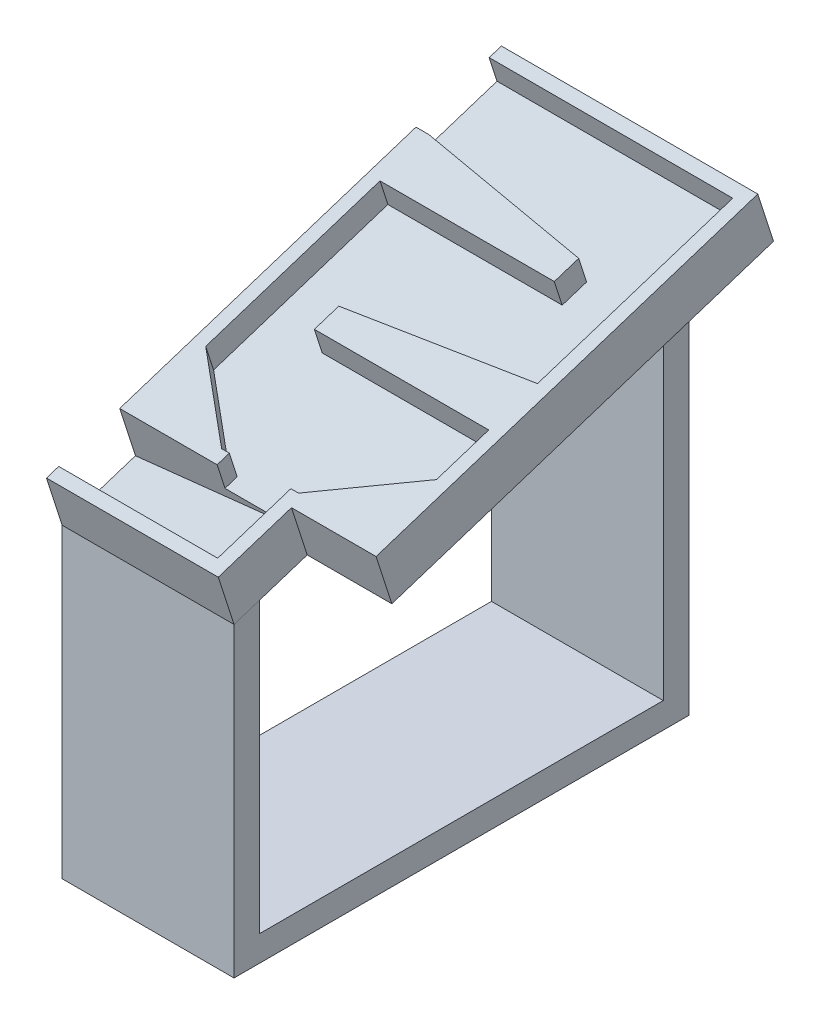
SolidWorks part; units mm, degrees
ref_plane "前基準面" through (0, 0, 0) normal (0, 0, 1) x (1, 0, 0)
ref_plane "上基準面" through (0, 0, 0) normal (0, 1, 0) x (1, 0, 0)
ref_plane "右基準面" through (0, 0, 0) normal (1, 0, 0) x (0, 0, -1)
sketch "草圖1" plane through (0, 0, 0) normal (1, 0, 0) x (0, 0, -1)
  line L0 (0, 0) -> (74.4311, 24)
  line L1 (74.4311, 24) -> (77.5, 14.4825)
  line L2 (77.5, 14.4825) -> (3.0689, -9.5175)
  line L3 (3.0689, -9.5175) -> (0, 0)
  dimension "D1" = 24
  dimension "D2" = 10
  dimension "D3" = 77.5
extrude "填料-伸長1" add sketch "草圖1" along normal blind 50
sketch "草圖2" plane through (0, 0, 0) normal (0, 0.9517, 0.3069) x (1, 0, 0)
  line L0 (0, 78.2048) -> (0, 0) construction
  line L1 (2.5, 75.7048) -> (47.5, 75.7048)
  line L2 (2.5, 75.7048) -> (2.5, 2.5)
  line L3 (2.5, 2.5) -> (47.5, 2.5)
  line L4 (47.5, 75.7048) -> (47.5, 2.5)
  line L5 (50, 78.2048) -> (50, 0) construction
  line L6 (50, 78.2048) -> (0, 78.2048) construction
  line L7 (50, 0) -> (0, 0) construction
  dimension "D1" = 2.5
  dimension "D2" = 2.5
  dimension "D3" = 2.5
  dimension "D4" = 2.5
extrude "除料-伸長1" cut sketch "草圖2" against normal blind 5
sketch "草圖3" plane through (0, -4.7587, -1.5344) normal (0, 0.9517, 0.3069) x (1, 0, 0)
  line L0 (2.5, 75.7048) -> (2.5, 2.5) construction
  line L1 (47.5, 75.7048) -> (2.5, 75.7048) construction
  line L2 (47.5, 2.5) -> (47.5, 75.7048) construction
  line L5 (50, 0) -> (0, 0) construction
  line L6 (0, 78.2048) -> (0, 0) construction
  circle A0 centre (18.5, 59.7048) radius 2.5
  circle A1 centre (21.75, 59.7048) radius 2.5
  circle A2 centre (25, 59.7048) radius 2.5
  circle A3 centre (28.25, 59.7048) radius 2.5
  circle A4 centre (31.5, 59.7048) radius 2.5
  circle A5 centre (19, 55.7229) radius 2.5
  circle A6 centre (22.25, 55.7229) radius 2.5
  circle A7 centre (25.5, 55.7229) radius 2.5
  circle A8 centre (28.75, 55.7229) radius 2.5
  circle A9 centre (32, 55.7229) radius 2.5
  circle A10 centre (19.5, 51.741) radius 2.5
  circle A11 centre (22.75, 51.741) radius 2.5
  circle A12 centre (26, 51.741) radius 2.5
  circle A13 centre (29.25, 51.741) radius 2.5
  circle A14 centre (32.5, 51.741) radius 2.5
  circle A15 centre (20, 47.7591) radius 2.5
  circle A16 centre (23.25, 47.7591) radius 2.5
  circle A17 centre (26.5, 47.7591) radius 2.5
  circle A18 centre (29.75, 47.7591) radius 2.5
  circle A19 centre (33, 47.7591) radius 2.5
  circle A20 centre (20.5, 43.7772) radius 2.5
  circle A21 centre (23.75, 43.7772) radius 2.5
  circle A22 centre (27, 43.7772) radius 2.5
  circle A23 centre (30.25, 43.7772) radius 2.5
  circle A24 centre (33.5, 43.7772) radius 2.5
  circle A25 centre (21, 39.7953) radius 2.5
  circle A26 centre (24.25, 39.7953) radius 2.5
  circle A27 centre (27.5, 39.7953) radius 2.5
  circle A28 centre (30.75, 39.7953) radius 2.5
  circle A29 centre (34, 39.7953) radius 2.5
  circle A35 centre (24.75, 35.8134) radius 2.5 [skipped]
  circle A36 centre (28, 35.8134) radius 2.5 [skipped]
  circle A37 centre (31.25, 35.8134) radius 2.5 [skipped]
  circle A38 centre (34.5, 35.8134) radius 2.5 [skipped]
  circle A39 centre (21.5, 35.8134) radius 2.5 [skipped]
  dimension "D1" = 5
  dimension "D5" = 16
  dimension "D2" = 16
  dimension "D3" = 16
  dimension "D7" = 39.7953
  dimension "D8" = 21
  dimension "D4" = 5
  dimension "D6" = 7
extrude "填料-伸長2" [suppressed] add sketch "草圖3" along normal blind 7
sketch "草圖7" plane through (0, -4.7587, -1.5344) normal (0, 0.9517, 0.3069) x (1, 0, 0)
  line L0 (2.5, 15) -> (17.5, 2.5)
  line L1 (2.5, 75.7048) -> (2.5, 2.5) construction
  line L2 (2.5, 2.5) -> (47.5, 2.5) construction
  line L3 (17.5, 2.5) -> (2.5, 2.5)
  line L4 (2.5, 2.5) -> (2.5, 15)
  line L5 (25, 0) -> (25, 169.8545) construction
  line L6 (50, 0) -> (0, 0) construction
  line L7 (47.5, 2.5) -> (47.5, 15)
  line L8 (32.5, 2.5) -> (47.5, 2.5)
  line L9 (47.5, 15) -> (32.5, 2.5)
  dimension "D1" = 15
  dimension "D2" = 12.5
extrude "填料-伸長3" add sketch "草圖7" along normal up to surface (5 mm away) up to face at (25, 12, -37.2156)
sketch "草圖9" plane through (0, 0.7672, -2.3794) normal (0, 0.3069, -0.9517) x (-1, 0, 0)
  line L0 (-50, 0) -> (0, 0) construction
  line L1 (-31, 0) -> (-19, 0)
  line L2 (-31, 0) -> (-31, -5)
  line L3 (-31, -5) -> (-19, -5)
  line L4 (-19, 0) -> (-19, -5)
  line L5 (-17.5, 0) -> (-32.5, 0) construction
  line L6 (-17.5, -5) -> (-32.5, -5) construction
  point P6 (-25, 0)
  dimension "D1" = 12
extrude "除料-伸長2" cut sketch "草圖9" against normal up to next
sketch "草圖11" plane through (0, 0, 0) normal (0, -0.3069, 0.9517) x (1, 0, 0)
  line L0 (0, -10) -> (31, -5)
  line L1 (31, -5) -> (31, -10)
  line L2 (50, -10) -> (0, -10) construction
  line L3 (31, -10) -> (0, -10)
extrude "填料-伸長4" add sketch "草圖11" along normal blind 15
sketch "草圖13" plane through (0, -4.6033, 14.2762) normal (0, -0.3069, 0.9517) x (1, 0, 0)
  line L1 (0, -10) -> (31, -10)
  line L2 (0, -10) -> (0, 0)
  line L3 (0, 0) -> (31, 0)
  line L4 (31, -10) -> (31, 0)
extrude "填料-伸長5" add sketch "草圖13" against normal blind 2.5
sketch "草圖14" plane through (31, 0, 0) normal (1, 0, 0) x (0, 0, -1)
  line L0 (-14.2762, -4.6033) -> (0, 0)
  line L1 (0, 0) -> (3.0689, -9.5175)
  line L2 (3.0689, -9.5175) -> (-11.2073, -14.1208)
  line L3 (-11.2073, -14.1208) -> (-14.2762, -4.6033)
extrude "填料-伸長6" add sketch "草圖14" along normal blind 2.5
sketch "草圖15" plane through (0, 0, 0) normal (-1, 0, 0) x (0, 0, 1)
  line L0 (-72.0518, 23.2328) -> (-73.5862, 18.4741)
  line L1 (-73.5862, 18.4741) -> (-59.31, 13.8708)
  line L2 (-73.5862, 18.4741) -> (-15.8106, -0.1554) construction
  line L3 (-59.31, 13.8708) -> (-57.7756, 18.6295)
  line L4 (-74.4311, 24) -> (0, 0) construction
  line L5 (-57.7756, 18.6295) -> (-72.0518, 23.2328)
  dimension "D1" = 15
extrude "除料-伸長3" cut sketch "草圖15" against normal up to next
sketch "草图1" plane through (0, -4.7587, -1.5344) normal (0, 0.9517, 0.3069) x (1, 0, 0)
  line L0 (2.5, 60.7048) -> (36.5, 55.7048)
  line L1 (36.5, 55.7048) -> (36.5, 50.7048)
  line L2 (36.5, 50.7048) -> (2.5, 50.7048)
  line L3 (2.5, 60.7048) -> (2.5, 15) construction
  line L4 (2.5, 50.7048) -> (2.5, 60.7048)
  line L5 (47.5, 15) -> (47.5, 75.7048) construction
  line L6 (47.5, 25.7048) -> (13.5, 25.7048)
  line L7 (47.5, 15) -> (47.5, 75.7048) construction
  line L8 (13.5, 25.7048) -> (13.5, 30.7048)
  line L9 (13.5, 30.7048) -> (47.5, 35.7048)
  line L10 (47.5, 35.7048) -> (47.5, 25.7048)
  point P3 (0, 0)
  point P17 (0, 0)
  dimension "D1" = 10
  dimension "D2" = 5
  dimension "D3" = 11
  dimension "D4" = 10
  dimension "D5" = 5
  dimension "D6" = 11
  dimension "D7" = 15
extrude "凸台-拉伸1" add sketch "草图1" along normal up to surface (5 mm away) up to face at (8.6429, 6.1995, -19.2266)
sketch "草图2" plane through (0, 0, 0) normal (-1, 0, 0) x (0, 0, 1)
  line L0 (-77.5, 14.4825) -> (-77.5, -73.8276)
  line L1 (-77.5, -73.8276) -> (11.2073, -73.8276)
  line L2 (11.2073, -73.8276) -> (11.2073, -14.1208)
  line L4 (-66.4481, 16.1724) -> (-66.4481, -73.8276) construction
  line L5 (-73.5862, 18.4741) -> (-59.31, 13.8708) construction
  line L6 (-72.5, 12.8703) -> (-72.5, -68.8276)
  line L7 (-3.0689, -9.5175) -> (-77.5, 14.4825) construction
  line L8 (-72.5, -68.8276) -> (6.2073, -68.8276)
  line L9 (6.2073, -68.8276) -> (6.2073, -12.5085)
  line L10 (8.828, -13.3535) -> (-3.0689, -9.5175) construction
  line L11 (-77.5, 14.4825) -> (-72.5, 12.8703)
  line L12 (6.2073, -12.5085) -> (11.2073, -14.1208)
  dimension "D1" = 90
  dimension "D2" = 5
  dimension "D3" = 5
  dimension "D4" = 5
extrude "凸台-拉伸2" add sketch "草图2" against normal up to surface (33.5 mm away) separate body up to face at (33.5, -7.0604, 5.6037)
